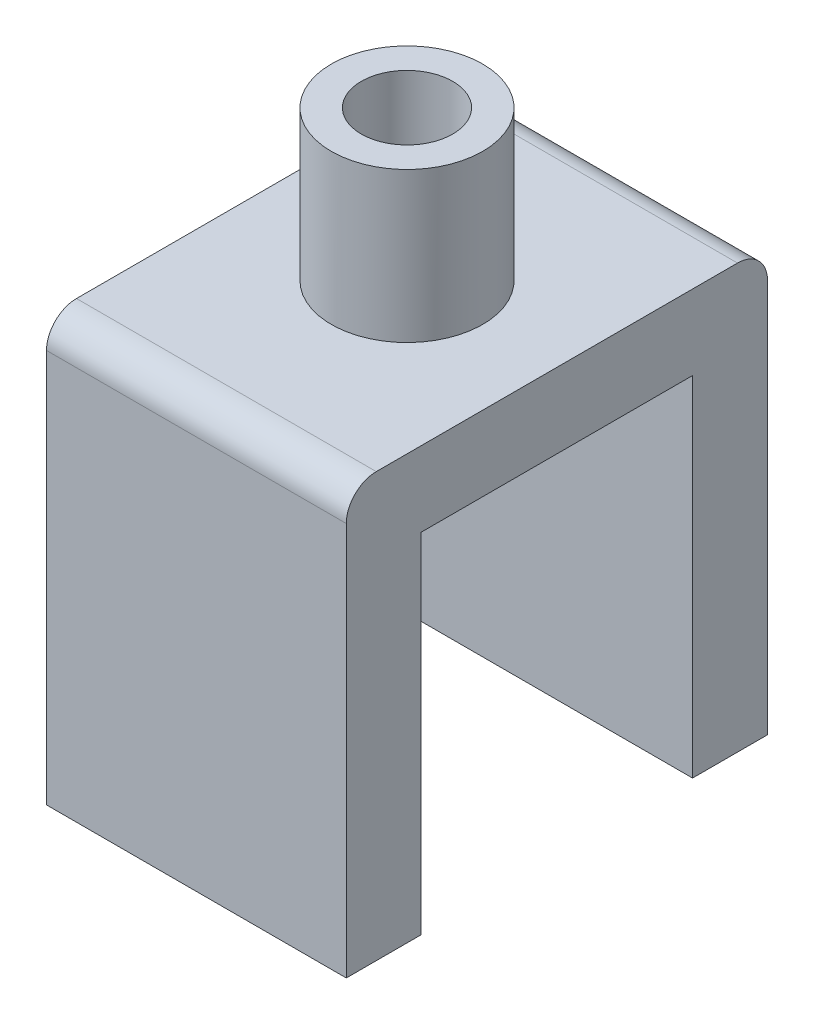
SolidWorks part; units mm, degrees
ref_plane "Alzado" through (0, 0, 0) normal (0, 0, 1) x (1, 0, 0)
ref_plane "Planta" through (0, 0, 0) normal (0, 1, 0) x (1, 0, 0)
ref_plane "Vista lateral" through (0, 0, 0) normal (1, 0, 0) x (0, 0, -1)
sketch "Croquis1" plane through (0, 0, 0) normal (1, 0, 0) x (0, 0, -1)
  line L0 (-9.05, 0) -> (9.05, 0)
  line L1 (9.05, 0) -> (9.05, -23.2572)
  line L2 (-9.05, 0) -> (-9.05, -23.2572)
  line L3 (14.05, 3) -> (14.05, -23.2572)
  line L4 (-12.05, 5) -> (12.05, 5)
  line L5 (-14.05, 3) -> (-14.05, -23.2572)
  line L6 (-14.05, -23.2572) -> (-9.05, -23.2572)
  line L7 (9.05, -23.2572) -> (14.05, -23.2572)
  line L8 (14.05, 5) -> (14.05, -23.2572) construction
  line L9 (-14.05, 5) -> (14.05, 5) construction
  line L10 (-14.05, 5) -> (-14.05, -23.2572) construction
  arc A0 (14.05, 3) -> (12.05, 5) centre (12.05, 3) ccw
  arc A1 (-12.05, 5) -> (-14.05, 3) centre (-12.05, 3) ccw
  dimension "D3" = 2
  dimension "D1" = 18.1
  dimension "D2" = 5
extrude "Saliente-Extruir1" add sketch "Croquis1" along normal mid plane 20
sketch "Croquis2" plane through (0, 5, 0) normal (0, 1, 0) x (1, 0, 0)
  circle A0 centre (0, 0) radius 3.05
  dimension "D1" = 6.1
extrude "Cortar-Extruir1" cut sketch "Croquis2" against normal through all
sketch "Croquis3" plane through (0, 5, 0) normal (0, 1, 0) x (1, 0, 0)
  circle A0 centre (0, 0) radius 3.05
  circle A1 centre (0, 0) radius 5.05
  dimension "D1" = 2
extrude "Saliente-Extruir2" add sketch "Croquis3" along normal blind 10
